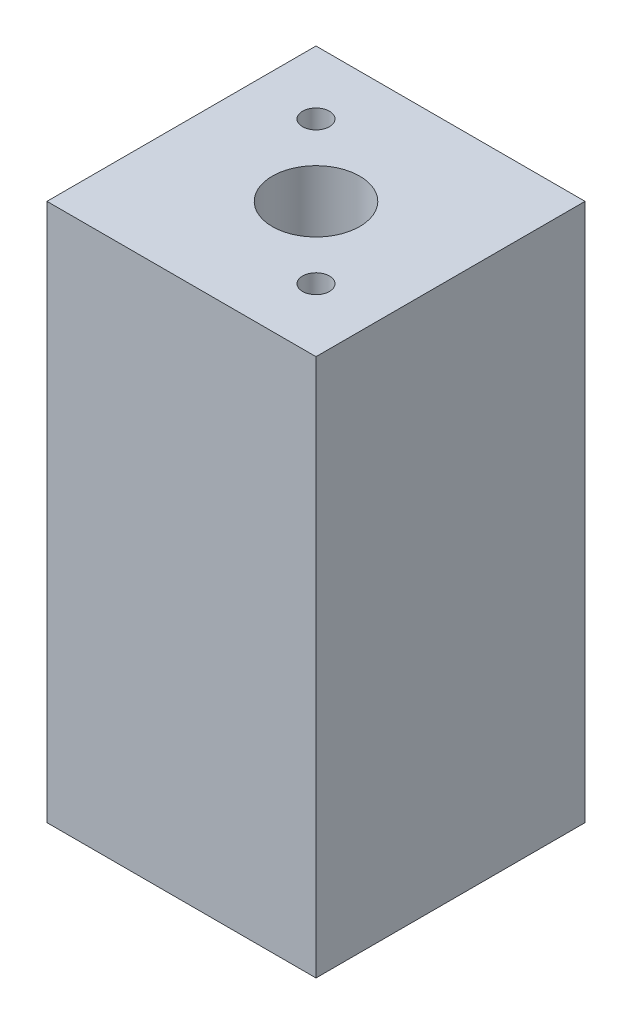
SolidWorks part; units mm, degrees
material "ABS"
ref_plane "Front" through (0, 0, 0) normal (0, 0, 1) x (1, 0, 0)
ref_plane "Top" through (0, 0, 0) normal (0, 1, 0) x (1, 0, 0)
ref_plane "Right" through (0, 0, 0) normal (1, 0, 0) x (0, 0, -1)
sketch "Esquisse1" plane through (0, 0, 0) normal (0, 1, 0) x (1, 0, 0)
  line L1 (-10, -10) -> (10, -10)
  line L2 (-10, -10) -> (-10, 10)
  line L3 (-10, 10) -> (10, 10)
  line L4 (10, -10) -> (10, 10)
  line L5 (-10, -10) -> (10, 10) construction
  line L6 (-10, 10) -> (10, -10) construction
  circle A0 centre (-5.3033, 5.3033) radius 1
  circle A1 centre (5.3033, -5.3033) radius 1
  circle A2 centre (0, 0) radius 3.25
  point P0 (0, 0)
  dimension "D2" = 2
  dimension "D3" = 15
  dimension "D4" = 6.5
  dimension "D1" = 20
extrude "Boss.-Extru.1" add sketch "Esquisse1" against normal blind 40
